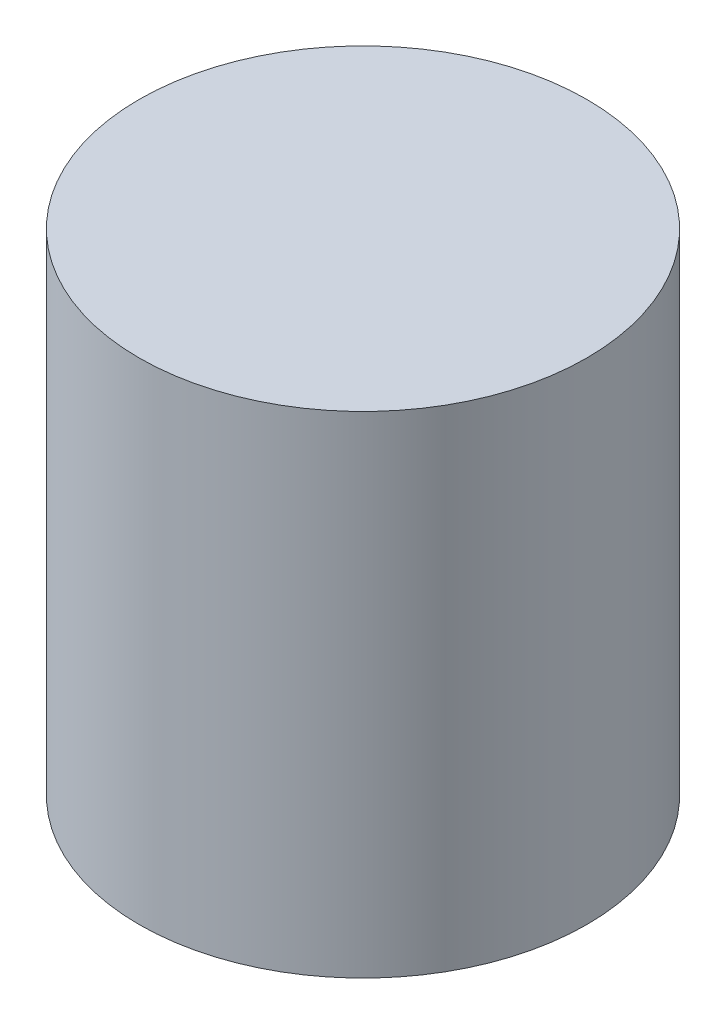
SolidWorks part; units mm, degrees
ref_plane "Front Plane" through (0, 0, 0) normal (0, 0, 1) x (1, 0, 0)
ref_plane "Top Plane" through (0, 0, 0) normal (0, 1, 0) x (1, 0, 0)
ref_plane "Right Plane" through (0, 0, 0) normal (1, 0, 0) x (0, 0, -1)
sketch "Sketch1" plane through (0, 0, 0) normal (0, 1, 0) x (1, 0, 0)
  circle A0 centre (0, 0) radius 3.65
  circle A1 centre (0, 0) radius 3.15
  dimension "D1" = 7.3
  dimension "D2" = 6.3
extrude "Boss-Extrude1" add sketch "Sketch1" along normal blind 8
sketch "Sketch2" plane through (0, 8, 0) normal (0, 1, 0) x (1, 0, 0)
  circle A0 centre (0, 0) radius 3.5189
extrude "Boss-Extrude2" add sketch "Sketch2" against normal blind 1
